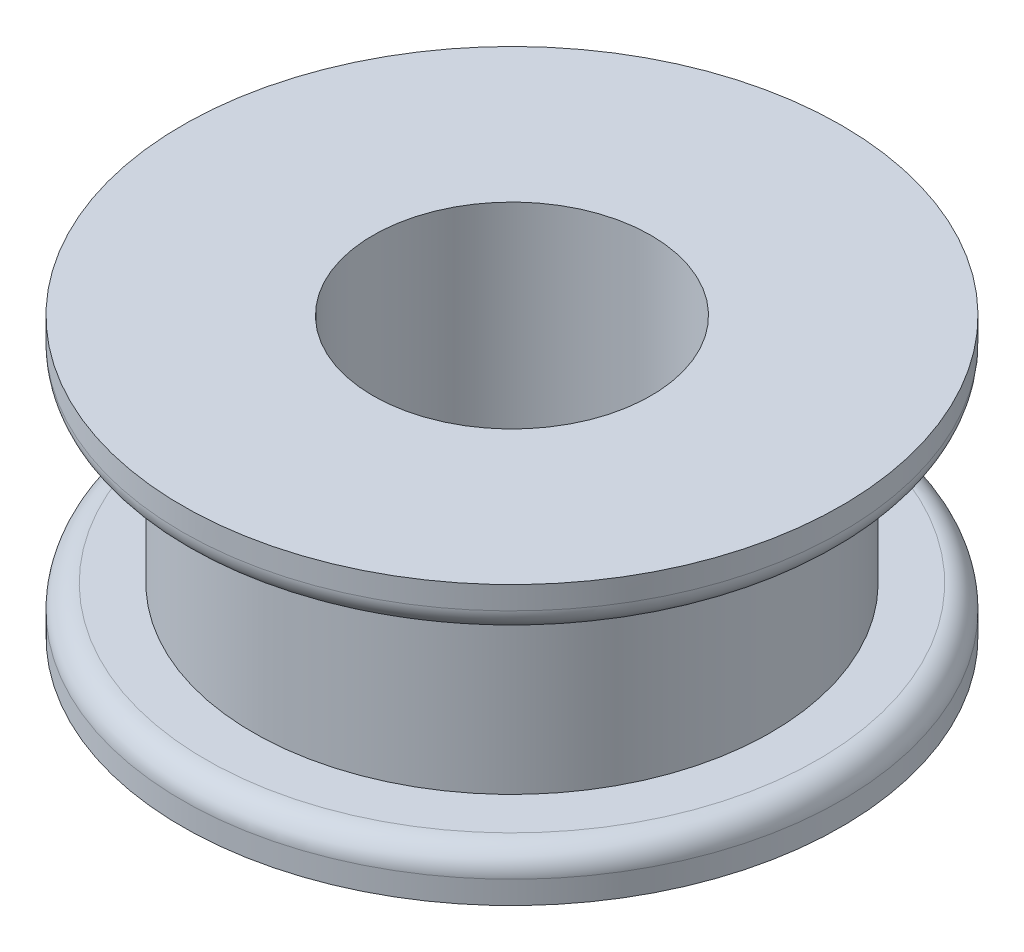
SolidWorks part; units mm, degrees
material "6061-T6 (SS)"
ref_plane "Front Plane" through (0, 0, 0) normal (1, 0, 0) x (0, 1, 0)
ref_plane "Top Plane" through (0, 0, 0) normal (0, 0, 1) x (0, 1, 0)
ref_plane "Right Plane" through (0, 0, 0) normal (0, 1, 0) x (-1, 0, 0)
sketch "Sketch1" plane through (0, 0, 0) normal (1, 0, 0) x (0, 1, 0)
  line L0 (-39.0416, 0) -> (31.6415, 0) construction
  line L1 (0, 3) -> (-6, 3)
  line L2 (-6, 3) -> (-6, 7.112)
  line L3 (-6, 7.112) -> (-5, 7.112)
  line L4 (-5, 7.112) -> (-5, 5.588)
  line L5 (-5, 5.588) -> (-1, 5.588)
  line L6 (-1, 5.588) -> (-1, 7.112)
  line L7 (-1, 7.112) -> (0, 7.112)
  line L8 (0, 7.112) -> (0, 3)
  dimension "D1" = 3
  dimension "D2" = 5.588
  dimension "D4" = 1.524
  dimension "D5" = 4
  dimension "D6" = 1
  dimension "D7" = 1
revolve "Revolve1" add sketch "Sketch1" angle 360 about L0
fillet "Fillet1" radius 0.508 2 edges at (0, -5, -7.112) (0, -1, -7.112)
equation "\"D1@Sketch1\"=3mm"
equation "\"D5@Sketch1\"=4mm"
equation "\"D6@Sketch1\"=1mm"
equation "\"D7@Sketch1\"=1mm"
